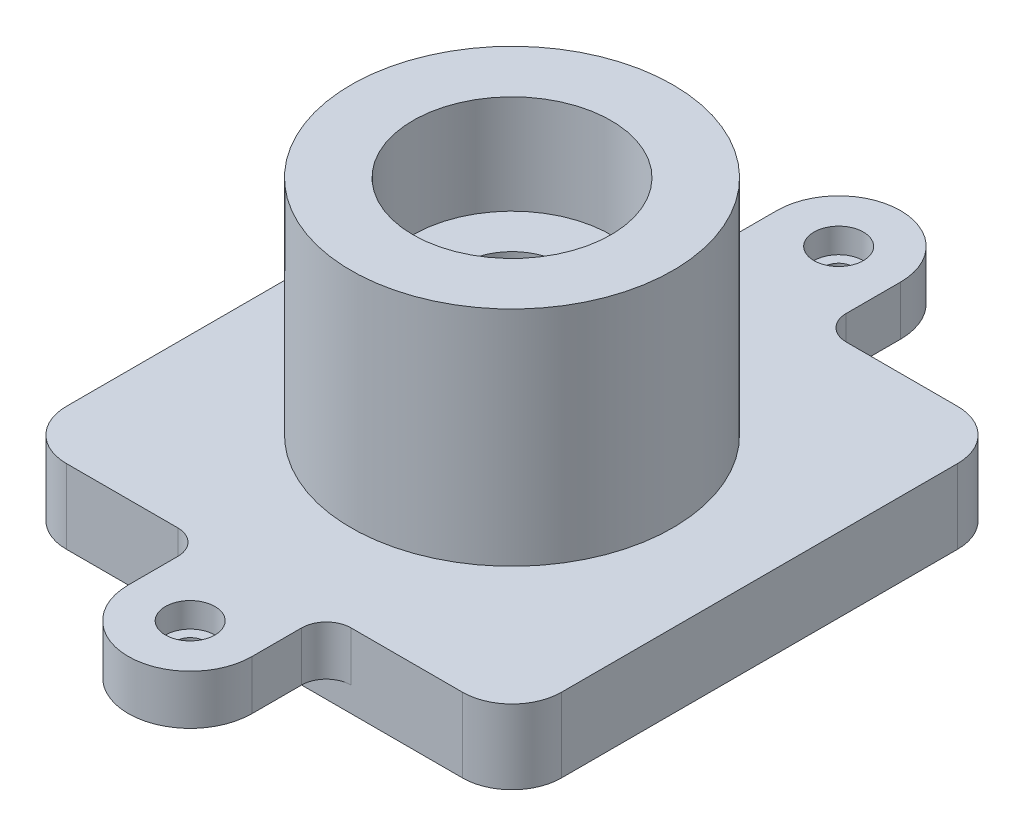
SolidWorks part; units mm, degrees
ref_plane "Front Plane" through (0, 0, 0) normal (0, 0, 1) x (1, 0, 0)
ref_plane "Top Plane" through (0, 0, 0) normal (0, 1, 0) x (1, 0, 0)
ref_plane "Right Plane" through (0, 0, 0) normal (1, 0, 0) x (0, 0, -1)
sketch "Sketch1" plane through (0, 0, 0) normal (0, 1, 0) x (1, 0, 0)
  line L0 (50, 0) -> (50, 116.093) construction
  line L1 (0, 0) -> (100, 0)
  line L2 (0, 0) -> (0, 100)
  line L3 (0, 100) -> (100, 100)
  line L4 (100, 0) -> (100, 100)
  line L5 (0, 50) -> (100, 50) construction
  dimension "D1" = 100
  dimension "D2" = 100
extrude "Boss-Extrude1" add sketch "Sketch1" along normal blind 15
sketch "Sketch3" plane through (0, 15, 0) normal (0, 1, 0) x (1, 0, 0)
  line L0 (50, 100) -> (50, 115.9751) construction
  line L1 (100, 100) -> (0, 100) construction
  line L2 (37.5, 100) -> (37.5, 115.9751)
  line L3 (62.5, 100) -> (62.5, 115.9751)
  line L4 (37.5, 100) -> (62.5, 100)
  line L5 (37.5, 115.9751) -> (62.5, 115.9751) construction
  line L6 (50, 128.4751) -> (50, 115.9751) construction
  line L9 (62.5, 0) -> (62.5, -15)
  line L10 (37.5, 0) -> (37.5, -15)
  line L11 (37.5, 0) -> (62.5, 0)
  arc A1 (62.5, 115.9751) -> (37.5, 115.9751) centre (50, 115.9751) ccw
  arc A3 (37.5, -15) -> (62.5, -15) centre (50, -15) ccw
  point P4 (50, 107.9875)
  point P10 (50, -7.5)
  dimension "D3" = 25
  dimension "D2" = 12.5
  dimension "D1" = 25
extrude "Boss-Extrude2" add sketch "Sketch3" against normal blind 10
hole_wizard "CBORE for M5 Hex Head Bolt2" positions "Sketch5" profile "Sketch6" counterbore size "M5" standard "ANSI Metric" end condition through all
sketch "Sketch5" plane through (0, 15, 0) normal (0, 1, 0) x (1, 0, 0)
  point P0 (50, 115.9751)
  point P4 (50, -15)
sketch "Sketch6" plane through (50, 15, -115.9751) normal (1, 0, 0) x (0, 0, 1)
  line L0 (0, 0) -> (0, 15)
  line L1 (0, 15) -> (2.9, 15)
  line L3 (2.9, 15) -> (2.9, 5)
  line L4 (2.9, 5) -> (5, 5)
  line L5 (5, 5) -> (5, 0)
  line L7 (5, 0) -> (0, 0)
  line L11 (0, -6.35) -> (0, 107.95) construction
  dimension "Thru Hole Dia." = 5.8
  dimension "Thru Hole Depth" = 15
  dimension "C'Bore Dia." = 10
  dimension "C'Bore Depth" = 5
fillet "Fillet1" radius 5 4 edges at (62.5, 10, -100) (37.5, 10, -100) (62.5, 10, 0) (37.5, 10, 0)
fillet "Fillet2" radius 10 4 edges at (100, 7.5, 0) (100, 7.5, -100) (0, 7.5, 0) (0, 7.5, -100)
sketch "Sketch11" plane through (0, 15, 0) normal (0, 1, 0) x (1, 0, 0)
  line L0 (50, 128.4751) -> (50, -27.5) construction
  line L1 (50, 50) -> (25.9186, 71.8251) construction
  line L2 (50, 50) -> (74.3147, 28.4351) construction
  line L3 (0, 50) -> (100, 50) construction
  line L4 (0, 90) -> (0, 10) construction
  line L5 (100, 10) -> (100, 90) construction
  line L6 (25.1508, 29.0533) -> (74.8492, 70.9467) construction
  arc A0 (37.5, -15) -> (62.5, -15) centre (50, -15) ccw construction
  circle A1 centre (50, 50) radius 32.5
extrude "Boss-Extrude3" add sketch "Sketch11" along normal blind 45 contours A1
hole_wizard "CBORE for M36 Hex Head Bolt2" positions "Sketch14" profile "Sketch15" counterbore size "M36" standard "ANSI Metric" end condition through all
sketch "Sketch14" plane through (0, 60, 0) normal (0, 1, 0) x (1, 0, 0)
  point P0 (50, 50)
sketch "Sketch15" plane through (50, 60, -50) normal (1, 0, 0) x (0, 0, 1)
  line L0 (0, 0) -> (0, 60)
  line L1 (0, 60) -> (10, 60)
  line L3 (10, 60) -> (10, 20)
  line L4 (10, 20) -> (20, 20)
  line L5 (20, 20) -> (20, 0)
  line L7 (20, 0) -> (0, 0)
  line L11 (0, -6.35) -> (0, 107.95) construction
  dimension "Thru Hole Dia." = 20
  dimension "Thru Hole Depth" = 60
  dimension "C'Bore Dia." = 40
  dimension "C'Bore Depth" = 20
ref_plane "Plane1" through (50, 0, 0) normal (1, 0, 0) x (0, 0, -1)
sketch "Sketch18" plane through (50, 0, 0) normal (1, 0, 0) x (0, 0, -1)
  line L0 (82.5, 60) -> (17.5, 60) construction
  arc A0 (82.6268, 47.5) -> (82.6268, 32.5) centre (82.6268, 40) ccw
  dimension "D1" = 20
